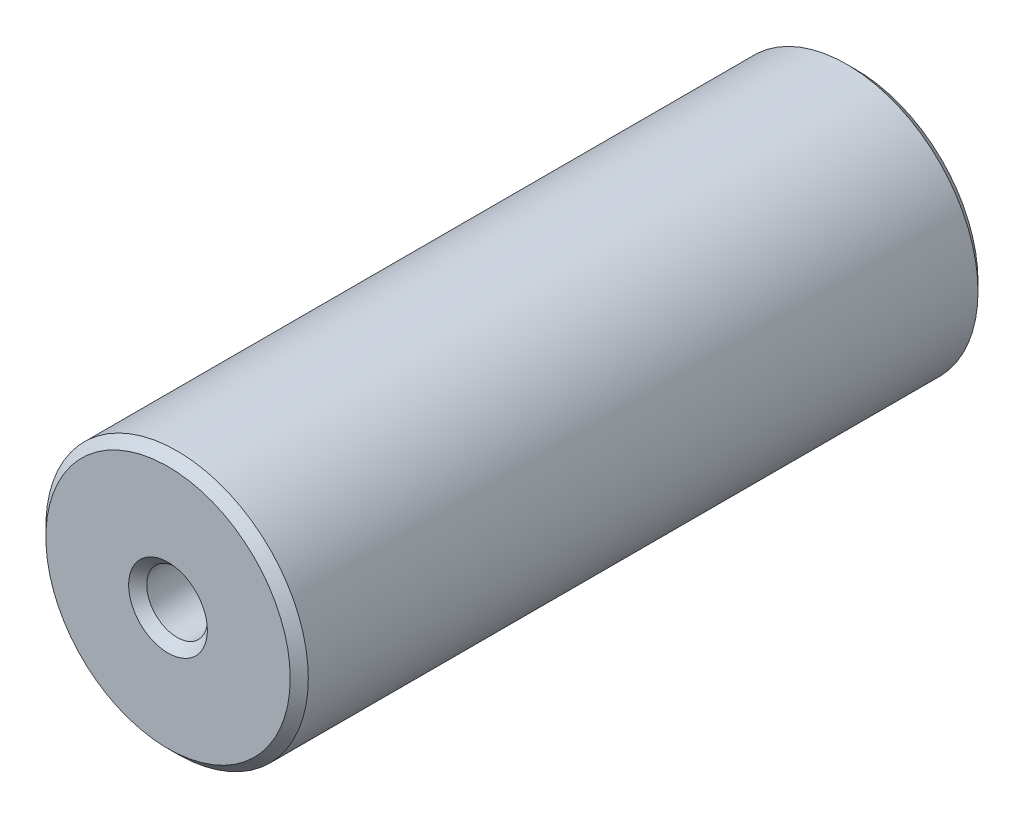
SolidWorks part; units mm, degrees
ref_plane "Plan de face" through (0, 0, 0) normal (0, 0, 1) x (1, 0, 0)
ref_plane "Plan de dessus" through (0, 0, 0) normal (0, 1, 0) x (1, 0, 0)
ref_plane "Plan de droite" through (0, 0, 0) normal (1, 0, 0) x (0, 0, -1)
sketch "Esquisse1" plane through (0, 0, 0) normal (0, 0, 1) x (1, 0, 0)
  circle A0 centre (0, 0) radius 3.35
  circle A1 centre (0, 0) radius 14.5
  dimension "D2" = 29
extrude "Boss.-Extru.1" add sketch "Esquisse1" along normal blind 76
chamfer "Chanfrein1" distance 1 angle 45 4 edges at (3.35, 0, 0) (3.35, 0, 76) (14.5, 0, 0) (14.5, 0, 76)
